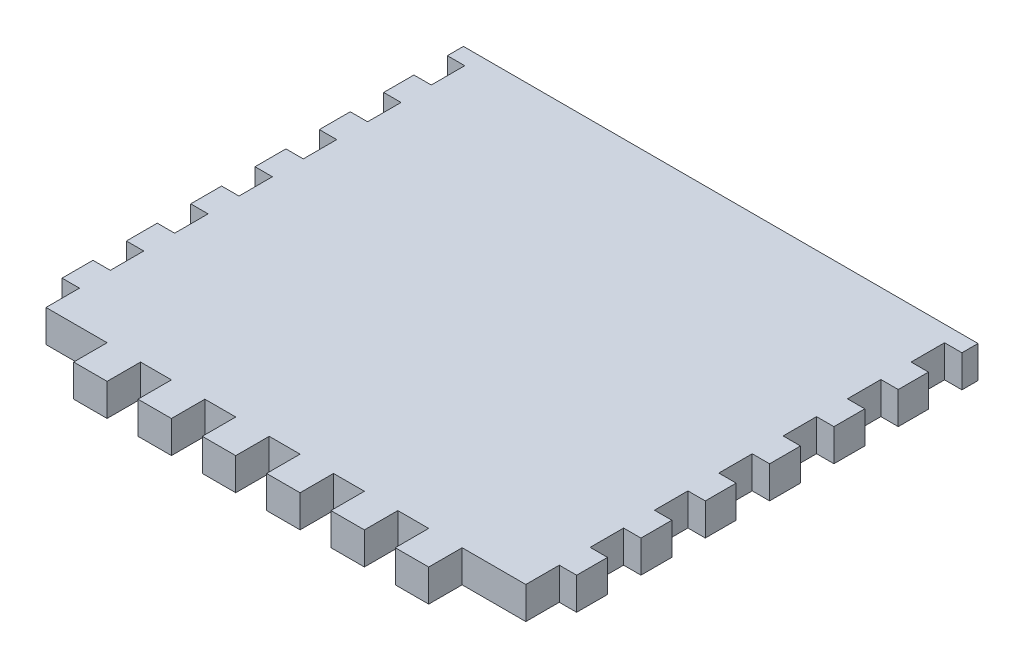
SolidWorks part; units mm, degrees
ref_plane "Front Plane" through (0, 0, 0) normal (0, 0, 1) x (1, 0, 0)
ref_plane "Top Plane" through (0, 0, 0) normal (0, 1, 0) x (1, 0, 0)
ref_plane "Right Plane" through (0, 0, 0) normal (1, 0, 0) x (0, 0, -1)
sketch "Sketch1" plane through (0, 0, 0) normal (0, 1, 0) x (1, 0, 0)
  line L1 (-50.8, -53.975) -> (50.8, -53.975)
  line L2 (-50.8, -53.975) -> (-50.8, 53.975)
  line L3 (-50.8, 53.975) -> (50.8, 53.975)
  line L4 (50.8, -53.975) -> (50.8, 53.975)
  line L5 (-50.8, -53.975) -> (50.8, 53.975) construction
  line L6 (-50.8, 53.975) -> (50.8, -53.975) construction
  line L11 (-41.275, -53.975) -> (41.275, 53.975) construction
  line L12 (-41.275, 53.975) -> (41.275, -53.975) construction
  point P0 (0, 0)
  point P5 (0, 0)
  dimension "D1" = 101.6
  dimension "D2" = 107.95
extrude "Boss-Extrude1" add sketch "Sketch1" along normal blind 6.35
sketch "Sketch2" plane through (0, 6.35, 0) normal (0, 1, 0) x (1, 0, 0)
  line L37 (22.098, -31.877) -> (28.194, -31.877)
  line L49 (28.194, -31.877) -> (28.194, -38.481)
  line L69 (0, 0) -> (0, -10.121) construction
  line L74 (-50.8, 53.975) -> (-50.8, -53.975) construction
  line L75 (-47.371, 44.196) -> (-50.8, 44.196)
  line L76 (-47.371, 44.196) -> (-47.371, 50.8)
  line L78 (-50.8, 44.196) -> (-50.8, 50.8)
  line L79 (-47.371, 38.227) -> (-50.8, 38.227)
  line L80 (-47.371, 38.227) -> (-47.371, 31.623)
  line L81 (-47.371, 31.623) -> (-50.8, 31.623)
  line L82 (-50.8, 38.227) -> (-50.8, 31.623)
  line L83 (-47.371, 25.527) -> (-50.8, 25.527)
  line L84 (-47.371, 25.527) -> (-47.371, 18.923)
  line L85 (-47.371, 18.923) -> (-50.8, 18.923)
  line L86 (-50.8, 25.527) -> (-50.8, 18.923)
  line L87 (-47.371, 12.827) -> (-50.8, 12.827)
  line L88 (-47.371, 12.827) -> (-47.371, 6.223)
  line L89 (-47.371, 6.223) -> (-50.8, 6.223)
  line L90 (-50.8, 12.827) -> (-50.8, 6.223)
  line L91 (-47.371, 0.127) -> (-50.8, 0.127)
  line L92 (-47.371, 0.127) -> (-47.371, -6.477)
  line L93 (-47.371, -6.477) -> (-50.8, -6.477)
  line L94 (-50.8, 0.127) -> (-50.8, -6.477)
  line L95 (-47.371, -12.573) -> (-50.8, -12.573)
  line L96 (-47.371, -12.573) -> (-47.371, -19.177)
  line L97 (-47.371, -19.177) -> (-50.8, -19.177)
  line L98 (-50.8, -12.573) -> (-50.8, -19.177)
  line L99 (-47.371, -25.273) -> (-50.8, -25.273)
  line L100 (-47.371, -25.273) -> (-47.371, -31.877)
  line L102 (-50.8, -25.273) -> (-50.8, -31.877)
  line L118 (50.8, -25.273) -> (50.8, -31.877)
  line L120 (47.371, -25.273) -> (47.371, -31.877)
  line L121 (47.371, -25.273) -> (50.8, -25.273)
  line L122 (50.8, -12.573) -> (50.8, -19.177)
  line L123 (47.371, -19.177) -> (50.8, -19.177)
  line L124 (47.371, -12.573) -> (47.371, -19.177)
  line L125 (47.371, -12.573) -> (50.8, -12.573)
  line L126 (50.8, 0.127) -> (50.8, -6.477)
  line L127 (47.371, -6.477) -> (50.8, -6.477)
  line L128 (47.371, 0.127) -> (47.371, -6.477)
  line L129 (47.371, 0.127) -> (50.8, 0.127)
  line L130 (50.8, 12.827) -> (50.8, 6.223)
  line L131 (47.371, 6.223) -> (50.8, 6.223)
  line L132 (47.371, 12.827) -> (47.371, 6.223)
  line L133 (47.371, 12.827) -> (50.8, 12.827)
  line L134 (50.8, 25.527) -> (50.8, 18.923)
  line L135 (47.371, 18.923) -> (50.8, 18.923)
  line L136 (47.371, 25.527) -> (47.371, 18.923)
  line L137 (47.371, 25.527) -> (50.8, 25.527)
  line L138 (50.8, 38.227) -> (50.8, 31.623)
  line L139 (47.371, 31.623) -> (50.8, 31.623)
  line L140 (47.371, 38.227) -> (47.371, 31.623)
  line L141 (47.371, 38.227) -> (50.8, 38.227)
  line L150 (-47.371, -37.973) -> (-50.8, -37.973) [skipped]
  line L151 (-47.371, -37.973) -> (-47.371, -44.577) [skipped]
  line L152 (-47.371, -44.577) -> (-50.8, -44.577) [skipped]
  line L153 (-50.8, -37.973) -> (-50.8, -44.577) [skipped]
  line L154 (-50.8, 50.8) -> (-47.371, 50.8)
  line L155 (50.8, 50.8) -> (47.371, 50.8)
  line L156 (50.8, 44.196) -> (50.8, 50.8)
  line L157 (47.371, 44.196) -> (47.371, 50.8)
  line L158 (47.371, 44.196) -> (50.8, 44.196)
  line L159 (-47.371, -31.877) -> (-35.306, -31.877)
  line L160 (-35.306, -31.877) -> (-35.306, -38.481)
  line L161 (-35.306, -38.481) -> (-28.702, -38.481)
  line L162 (-28.702, -38.481) -> (-28.702, -31.877)
  line L163 (-28.702, -31.877) -> (-22.606, -31.877)
  line L164 (-22.606, -31.877) -> (-22.606, -38.481)
  line L165 (-22.606, -38.481) -> (-16.002, -38.481)
  line L166 (-16.002, -38.481) -> (-16.002, -31.877)
  line L167 (-16.002, -31.877) -> (-9.906, -31.877)
  line L168 (-9.906, -31.877) -> (-9.906, -38.481)
  line L169 (-9.906, -38.481) -> (-3.302, -38.481)
  line L170 (-3.302, -38.481) -> (-3.302, -31.877)
  line L171 (-3.302, -31.877) -> (2.794, -31.877)
  line L172 (2.794, -31.877) -> (2.794, -38.481)
  line L173 (2.794, -38.481) -> (9.398, -38.481)
  line L174 (9.398, -38.481) -> (9.398, -31.877)
  line L175 (9.398, -31.877) -> (15.494, -31.877)
  line L176 (15.494, -31.877) -> (15.494, -38.481)
  line L177 (15.494, -38.481) -> (22.098, -38.481)
  line L178 (22.098, -38.481) -> (22.098, -31.877)
  line L180 (-50.8, -31.877) -> (-50.8, -53.975)
  line L181 (-47.371, -31.877) -> (-50.8, -31.877) [skipped]
  line L182 (-50.8, -53.975) -> (50.8, -53.975)
  line L183 (50.8, -53.975) -> (50.8, -31.877)
  line L184 (28.194, -38.481) -> (34.798, -38.481)
  line L185 (34.798, -38.481) -> (34.798, -31.877)
  line L186 (34.798, -31.877) -> (47.371, -31.877)
  point P0 (-28.702, -35.179)
  dimension "D2" = 15.494
  dimension "D3" = 6.604
  dimension "D5" = 6.096
  dimension "D8" = 3.429
  dimension "D10" = 6.604
  dimension "D4" = 6.096
  dimension "D14" = 5.969
  dimension "D11" = 7
extrude "Cut-Extrude1" cut sketch "Sketch2" against normal through all both and the other way through all
